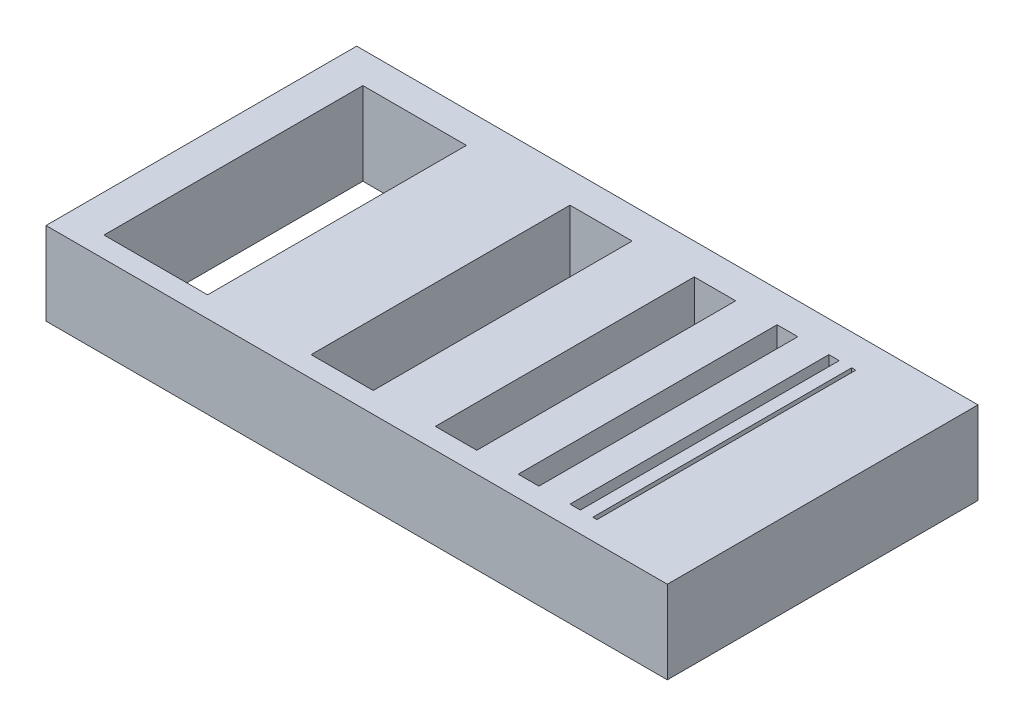
SolidWorks part; units mm, degrees
ref_plane "Front Plane" through (0, 0, 0) normal (0, 0, 1) x (1, 0, 0)
ref_plane "Top Plane" through (0, 0, 0) normal (0, 1, 0) x (1, 0, 0)
ref_plane "Right Plane" through (0, 0, 0) normal (1, 0, 0) x (0, 0, -1)
sketch "Sketch2" plane through (0, 0, 0) normal (0, 1, 0) x (1, 0, 0)
  line L1 (0, 0) -> (150, 0)
  line L2 (0, 0) -> (0, 75)
  line L3 (0, 75) -> (150, 75)
  line L4 (150, 0) -> (150, 75)
  line L5 (9, 67.5) -> (34, 67.5)
  line L6 (9, 67.5) -> (9, 5)
  line L7 (9, 5) -> (34, 5)
  line L8 (34, 67.5) -> (34, 5)
  line L9 (59, 67.5) -> (74, 67.5)
  line L10 (59, 67.5) -> (59, 5)
  line L11 (59, 5) -> (74, 5)
  line L12 (74, 67.5) -> (74, 5)
  line L13 (89, 67.5) -> (99, 67.5)
  line L14 (89, 67.5) -> (89, 5)
  line L15 (89, 5) -> (99, 5)
  line L16 (99, 67.5) -> (99, 5)
  line L17 (109, 67.5) -> (114, 67.5)
  line L18 (109, 67.5) -> (109, 5)
  line L19 (109, 5) -> (114, 5)
  line L20 (114, 67.5) -> (114, 5)
  line L21 (121.5, 67.5) -> (124, 67.5)
  line L22 (121.5, 67.5) -> (121.5, 5)
  line L23 (121.5, 5) -> (124, 5)
  line L24 (124, 67.5) -> (124, 5)
  line L25 (127, 67.5) -> (128, 67.5)
  line L26 (127, 67.5) -> (127, 5)
  line L27 (127, 5) -> (128, 5)
  line L28 (128, 67.5) -> (128, 5)
  point P0 (0, 0.0637)
  point P1 (150, 75)
  point P2 (0, 75)
  point P3 (150, 0)
  point P29 (150, -0.0592)
  point P31 (150, 75)
  point P34 (150, 0)
  point P37 (0, 0)
  point P38 (149.9254, 75)
  point P40 (0, 75)
  point P41 (0.1551, 75)
  point P42 (150, 0.0494)
  dimension "D1" = 150
  dimension "D2" = 25
  dimension "D3" = 15
  dimension "D4" = 10
  dimension "D5" = 5
  dimension "D6" = 2.5
  dimension "D7" = 1
  dimension "D8" = 5
  dimension "D9" = 7.5
  dimension "D10" = 9
  dimension "D11" = 25
  dimension "D12" = 15
  dimension "D13" = 10
  dimension "D14" = 7.5
  dimension "D15" = 3
  dimension "D16" = 75
extrude "Boss-Extrude1" add sketch "Sketch2" along normal blind 20
